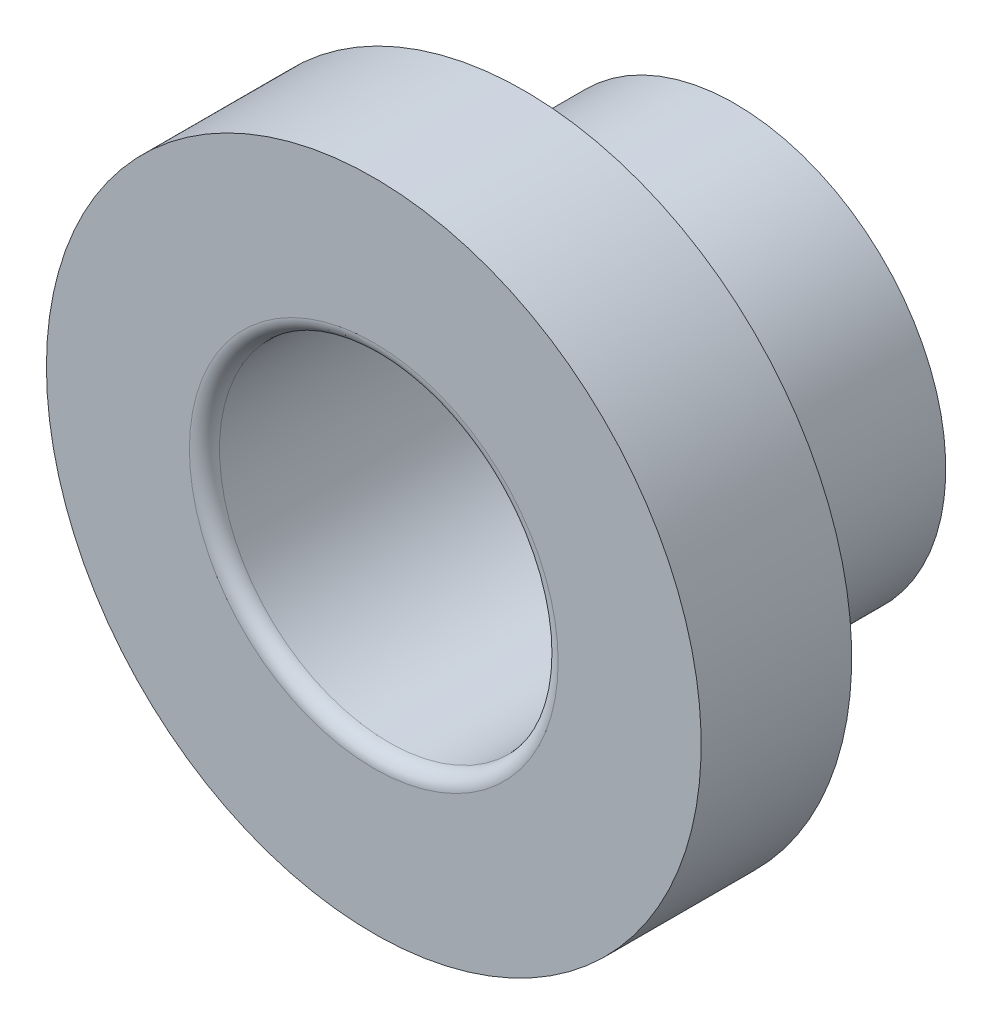
SolidWorks part; units mm, degrees
ref_plane "Front Plane" through (0, 0, 0) normal (0, 0, 1) x (1, 0, 0)
ref_plane "Top Plane" through (0, 0, 0) normal (0, 1, 0) x (1, 0, 0)
ref_plane "Right Plane" through (0, 0, 0) normal (1, 0, 0) x (0, 0, -1)
ref_plane "Plane1" through (0, 0, 0) normal (0, -1, 0) x (1, 0, 0)
sketch "Sketch1" plane through (0, 0, 0) normal (0, -1, 0) x (1, 0, 0)
  line L0 (0, -0.5989) -> (0, -1.0769) construction
  line L1 (0, 0) -> (1.4, 0)
  line L2 (1.4, 0) -> (1.4, 1.4)
  line L3 (1.4, 1.4) -> (2.175, 1.4)
  line L4 (2.175, 1.4) -> (2.175, 2.4)
  line L5 (2.175, 2.4) -> (0, 2.4)
  line L6 (0, 2.4) -> (0, 0)
  point P1 (1.4912, 1.4)
  point P8 (0.8582, 1.4)
  dimension "D1" = 1
  dimension "D2" = 2.8
  dimension "D3" = 4.35
  dimension "D4" = 2.4
revolve "Revolve1" add sketch "Sketch1" angle 360 about L6
hole_wizard "HoleWzd1" positions "Sketch2" profile "Sketch3" legacy end condition through all
sketch "Sketch2" plane through (0, 0, 2.4) normal (0, 0, 1) x (1, 0, 0)
  point P0 (0, 0)
sketch "Sketch3" plane through (0, 0, 2.4) normal (1, 0, 0) x (0, -1, 0)
  line L0 (0, 0) -> (0, 2.4)
  line L1 (0, 2.4) -> (1.125, 2.4)
  line L2 (1.125, 2.4) -> (1.125, 0)
  line L3 (1.125, 0) -> (0, 0)
  line L4 (0, 110) -> (0, -10) construction
  dimension "Diameter" = 2.25
  dimension "Depth" = 2.4
fillet "Fillet1" radius 0.1 1 edges at (1.125, 0, 2.4)
